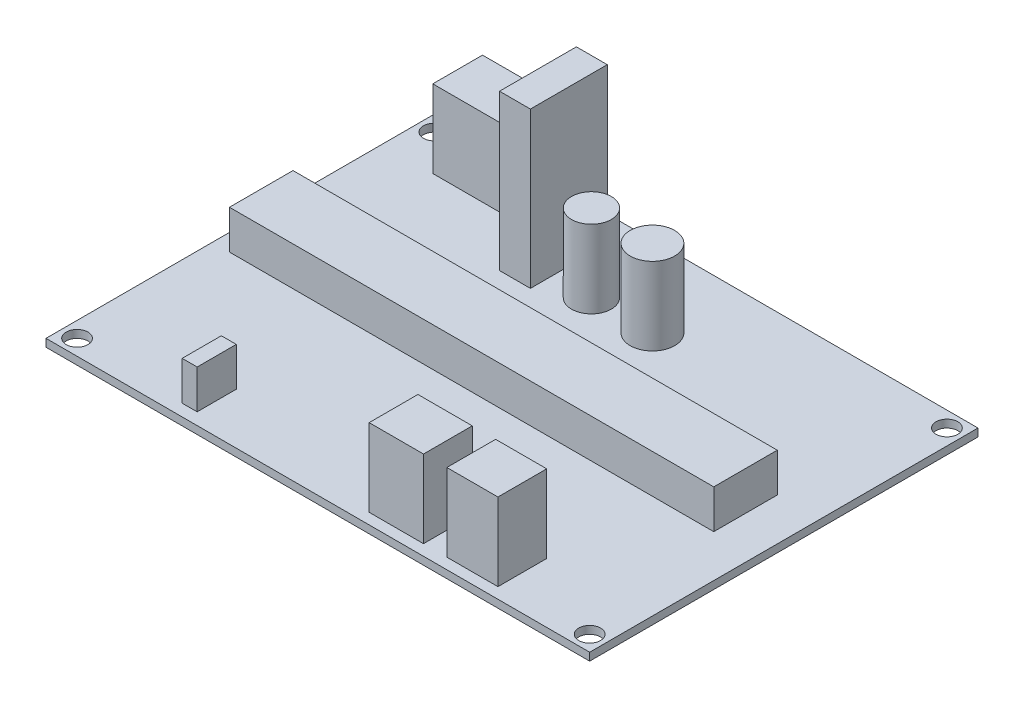
SolidWorks part; units mm, degrees
ref_plane "Front Plane" through (0, 0, 0) normal (0, 0, 1) x (1, 0, 0)
ref_plane "Top Plane" through (0, 0, 0) normal (0, 1, 0) x (1, 0, 0)
ref_plane "Right Plane" through (0, 0, 0) normal (1, 0, 0) x (0, 0, -1)
sketch "Sketch1" plane through (0, 0, 0) normal (0, 1, 0) x (1, 0, 0)
  line L1 (0, 0) -> (70, 0)
  line L2 (0, 0) -> (0, 50)
  line L3 (0, 50) -> (70, 50)
  line L4 (70, 0) -> (70, 50)
  dimension "D1" = 70
  dimension "D2" = 50
extrude "Boss-Extrude1" add sketch "Sketch1" along normal blind 1
sketch "Sketch2" plane through (0, 1, 0) normal (0, 1, 0) x (1, 0, 0)
  line L0 (2, 25) -> (0, 25) construction
  line L1 (2, 48) -> (68, 48) construction
  line L2 (2, 48) -> (2, 2) construction
  line L3 (2, 2) -> (68, 2) construction
  line L4 (68, 48) -> (68, 2) construction
  line L5 (0, 50) -> (0, 0) construction
  line L6 (35, 48) -> (35, 50) construction
  line L7 (70, 50) -> (0, 50) construction
  line L8 (35, 0) -> (35, 2) construction
  line L9 (0, 0) -> (70, 0) construction
  line L10 (68, 25) -> (70, 25) construction
  line L11 (70, 0) -> (70, 50) construction
  circle A0 centre (2, 48) radius 1.4
  circle A1 centre (68, 48) radius 1.4
  circle A2 centre (68, 2) radius 1.4
  circle A3 centre (2, 2) radius 1.4
  dimension "D3" = 2.8
  dimension "D1" = 2
  dimension "D2" = 2
extrude "Cut-Extrude1" cut sketch "Sketch2" against normal through all
sketch "Sketch3" plane through (0, 1, 0) normal (0, 1, 0) x (1, 0, 0)
  line L17 (40.2044, 1.4037) -> (47.2014, 1.4037)
  line L18 (40.2044, 1.4037) -> (40.2044, 7.6836)
  line L19 (40.2044, 7.6836) -> (47.2014, 7.6836)
  line L20 (47.2014, 1.4037) -> (47.2014, 7.6836)
  line L21 (50.2078, 1.4037) -> (56.7864, 1.4037)
  line L22 (50.2078, 1.4037) -> (50.2078, 7.6836)
  line L23 (50.2078, 7.6836) -> (56.7864, 7.6836)
  line L24 (56.7864, 1.4037) -> (56.7864, 7.6836)
  line L26 (6.5223, 49.6827) -> (18.0874, 49.6827)
  line L27 (6.5223, 49.6827) -> (6.5223, 43.2779)
  line L28 (6.5223, 43.2779) -> (18.0874, 43.2779)
  line L29 (18.0874, 49.6827) -> (18.0874, 43.2779)
  circle A0 centre (30.5779, 39.6459) radius 2.5647
  circle A1 centre (38.435, 39.6459) radius 2.8605
extrude "Boss-Extrude2" add sketch "Sketch3" along normal blind 10
sketch "Sketch5" plane through (0, 1, 0) normal (0, 1, 0) x (1, 0, 0)
  line L1 (2.1938, 21.4279) -> (64.5498, 21.4279)
  line L2 (2.1938, 21.4279) -> (2.1938, 29.6079)
  line L3 (2.1938, 29.6079) -> (64.5498, 29.6079)
  line L4 (64.5498, 21.4279) -> (64.5498, 29.6079)
  line L5 (16.0004, 1.5329) -> (17.9272, 1.5329)
  line L6 (16.0004, 1.5329) -> (16.0004, 6.5758)
  line L7 (16.0004, 6.5758) -> (17.9272, 6.5758)
  line L8 (17.9272, 1.5329) -> (17.9272, 6.5758)
extrude "Boss-Extrude3" add sketch "Sketch5" along normal blind 5
sketch "Sketch6" plane through (0, 1, 0) normal (0, 1, 0) x (1, 0, 0)
  line L1 (25.6176, 36.7515) -> (21.642, 36.7515)
  line L2 (25.6176, 36.7515) -> (25.6176, 46.6494)
  line L3 (25.6176, 46.6494) -> (21.642, 46.6494)
  line L4 (21.642, 36.7515) -> (21.642, 46.6494)
extrude "Boss-Extrude4" add sketch "Sketch6" along normal blind 20
equation "\"2xm\"=0.19685"
